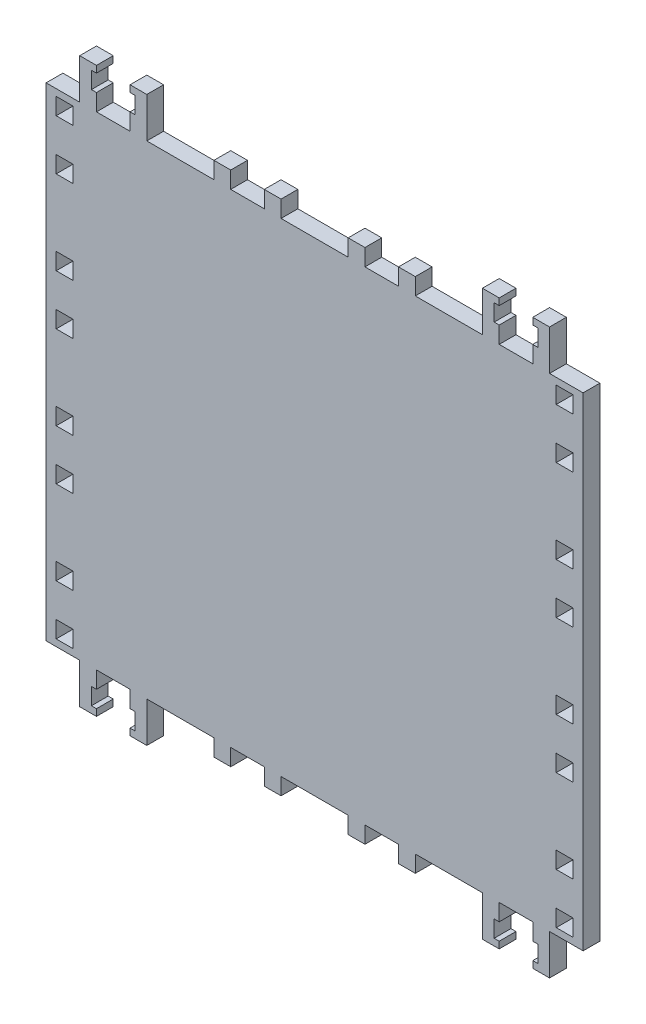
SolidWorks part; units mm, degrees
ref_plane "Plan de face" through (0, 0, 0) normal (0, 0, 1) x (1, 0, 0)
ref_plane "Plan de dessus" through (0, 0, 0) normal (0, 1, 0) x (1, 0, 0)
ref_plane "Plan de droite" through (0, 0, 0) normal (1, 0, 0) x (0, 0, -1)
sketch "Esquisse1" plane through (0, 0, 0) normal (0, 0, 1) x (1, 0, 0)
  line L0 (0, 0) -> (0, 72) construction
  line L1 (-30.7346, 72) -> (18.6998, 72) construction
  line L2 (-80, 144) -> (-70, 144)
  line L3 (-80, 144) -> (-80, 0) construction
  line L4 (-50, 144) -> (-30, 144)
  line L5 (-80, 0) -> (-70, 0)
  line L6 (50, 144) -> (30, 144)
  line L8 (80, 144) -> (70, 144)
  line L9 (10, 144) -> (-10, 144)
  line L10 (80, 0) -> (70, 0)
  line L11 (10, 0) -> (-10, 0)
  line L12 (50, 0) -> (30, 0)
  line L13 (-50, 0) -> (-30, 0)
  line L19 (-80, 0) -> (-80, 144)
  line L26 (80, 144) -> (80, 0)
  point P30 (72, 139.5)
  line B0 (20, 144) -> (20, 132.8925) construction
  line B1 (20, 144) -> (25, 144)
  line B2 (25, 149) -> (30, 149)
  line B3 (30, 149) -> (30, 144)
  line B4 (25, 149) -> (25, 144)
  line B5 (20, 144) -> (15, 144)
  line B6 (15, 144) -> (15, 149)
  line B7 (15, 149) -> (10, 149)
  line B8 (10, 149) -> (10, 144)
  line B9 (-20, 144) -> (-20, 132.8925) construction
  line B10 (-20, 144) -> (-25, 144)
  line B11 (-25, 149) -> (-30, 149)
  line B12 (-30, 149) -> (-30, 144)
  line B13 (-25, 149) -> (-25, 144)
  line B14 (-20, 144) -> (-15, 144)
  line B15 (-15, 144) -> (-15, 149)
  line B16 (-15, 149) -> (-10, 149)
  line B17 (-10, 149) -> (-10, 144)
  line B18 (20, 0) -> (20, 11.1075) construction
  line B19 (20, 0) -> (25, 0)
  line B20 (25, -5) -> (30, -5)
  line B21 (30, -5) -> (30, 0)
  line B22 (25, -5) -> (25, 0)
  line B23 (20, 0) -> (15, 0)
  line B24 (15, 0) -> (15, -5)
  line B25 (15, -5) -> (10, -5)
  line B26 (10, -5) -> (10, 0)
  line B27 (-20, 0) -> (-20, 11.1075) construction
  line B28 (-20, 0) -> (-25, 0)
  line B29 (-25, -5) -> (-30, -5)
  line B30 (-30, -5) -> (-30, 0)
  line B31 (-25, -5) -> (-25, 0)
  line B32 (-20, 0) -> (-15, 0)
  line B33 (-15, 0) -> (-15, -5)
  line B34 (-15, -5) -> (-10, -5)
  line B35 (-10, -5) -> (-10, 0)
  line B36 (74.5, 127) -> (74.5, 137) construction
  line B37 (77, 127) -> (77, 122)
  line B38 (77, 127) -> (72, 127)
  line B39 (72, 127) -> (72, 122)
  line B40 (77, 122) -> (72, 122)
  line B41 (77, 137) -> (77, 142)
  line B42 (77, 137) -> (72, 137)
  line B43 (72, 137) -> (72, 142)
  line B44 (77, 142) -> (72, 142)
  line B45 (74.5, 132) -> (80.7802, 132) construction
  circle B46 centre (74.5, 132) radius 1.5 construction
  line B47 (77, 142) -> (72, 137) construction
  line B48 (77, 127) -> (72, 122) construction
  line B49 (74.5, 87) -> (74.5, 97) construction
  line B50 (77, 87) -> (77, 82)
  line B51 (77, 87) -> (72, 87)
  line B52 (72, 87) -> (72, 82)
  line B53 (77, 82) -> (72, 82)
  line B54 (77, 97) -> (77, 102)
  line B55 (77, 97) -> (72, 97)
  line B56 (72, 97) -> (72, 102)
  line B57 (77, 102) -> (72, 102)
  line B58 (74.5, 92) -> (80.7802, 92) construction
  circle B59 centre (74.5, 92) radius 1.5 construction
  line B60 (77, 102) -> (72, 97) construction
  line B61 (77, 87) -> (72, 82) construction
  line B62 (74.5, 17) -> (74.5, 7) construction
  line B63 (77, 17) -> (77, 22)
  line B64 (77, 17) -> (72, 17)
  line B65 (72, 17) -> (72, 22)
  line B66 (77, 22) -> (72, 22)
  line B67 (77, 7) -> (77, 2)
  line B68 (77, 7) -> (72, 7)
  line B69 (72, 7) -> (72, 2)
  line B70 (77, 2) -> (72, 2)
  line B71 (74.5, 12) -> (80.7802, 12) construction
  circle B72 centre (74.5, 12) radius 1.5 construction
  line B73 (77, 2) -> (72, 7) construction
  line B74 (77, 17) -> (72, 22) construction
  line B75 (74.5, 57) -> (74.5, 47) construction
  line B76 (77, 57) -> (77, 62)
  line B77 (77, 57) -> (72, 57)
  line B78 (72, 57) -> (72, 62)
  line B79 (77, 62) -> (72, 62)
  line B80 (77, 47) -> (77, 42)
  line B81 (77, 47) -> (72, 47)
  line B82 (72, 47) -> (72, 42)
  line B83 (77, 42) -> (72, 42)
  line B84 (74.5, 52) -> (80.7802, 52) construction
  circle B85 centre (74.5, 52) radius 1.5 construction
  line B86 (77, 42) -> (72, 47) construction
  line B87 (77, 57) -> (72, 62) construction
  line B88 (-74.5, 57) -> (-74.5, 47) construction
  line B89 (-77, 57) -> (-77, 62)
  line B90 (-77, 57) -> (-72, 57)
  line B91 (-72, 57) -> (-72, 62)
  line B92 (-77, 62) -> (-72, 62)
  line B93 (-77, 47) -> (-77, 42)
  line B94 (-77, 47) -> (-72, 47)
  line B95 (-72, 47) -> (-72, 42)
  line B96 (-77, 42) -> (-72, 42)
  line B97 (-74.5, 52) -> (-80.7802, 52) construction
  circle B98 centre (-74.5, 52) radius 1.5 construction
  line B99 (-77, 42) -> (-72, 47) construction
  line B100 (-77, 57) -> (-72, 62) construction
  line B101 (-74.5, 127) -> (-74.5, 137) construction
  line B102 (-77, 127) -> (-77, 122)
  line B103 (-77, 127) -> (-72, 127)
  line B104 (-72, 127) -> (-72, 122)
  line B105 (-77, 122) -> (-72, 122)
  line B106 (-77, 137) -> (-77, 142)
  line B107 (-77, 137) -> (-72, 137)
  line B108 (-72, 137) -> (-72, 142)
  line B109 (-77, 142) -> (-72, 142)
  line B110 (-74.5, 132) -> (-80.7802, 132) construction
  circle B111 centre (-74.5, 132) radius 1.5 construction
  line B112 (-77, 142) -> (-72, 137) construction
  line B113 (-77, 127) -> (-72, 122) construction
  line B114 (-74.5, 17) -> (-74.5, 7) construction
  line B115 (-77, 17) -> (-77, 22)
  line B116 (-77, 17) -> (-72, 17)
  line B117 (-72, 17) -> (-72, 22)
  line B118 (-77, 22) -> (-72, 22)
  line B119 (-77, 7) -> (-77, 2)
  line B120 (-77, 7) -> (-72, 7)
  line B121 (-72, 7) -> (-72, 2)
  line B122 (-77, 2) -> (-72, 2)
  line B123 (-74.5, 12) -> (-80.7802, 12) construction
  circle B124 centre (-74.5, 12) radius 1.5 construction
  line B125 (-77, 2) -> (-72, 7) construction
  line B126 (-77, 17) -> (-72, 22) construction
  line B127 (-74.5, 87) -> (-74.5, 97) construction
  line B128 (-77, 87) -> (-77, 82)
  line B129 (-77, 87) -> (-72, 87)
  line B130 (-72, 87) -> (-72, 82)
  line B131 (-77, 82) -> (-72, 82)
  line B132 (-77, 97) -> (-77, 102)
  line B133 (-77, 97) -> (-72, 97)
  line B134 (-72, 97) -> (-72, 102)
  line B135 (-77, 102) -> (-72, 102)
  line B136 (-74.5, 92) -> (-80.7802, 92) construction
  circle B137 centre (-74.5, 92) radius 1.5 construction
  line B138 (-77, 102) -> (-72, 97) construction
  line B139 (-77, 87) -> (-72, 82) construction
  line B140 (-60, 0) -> (-60, 11.865) construction
  line B141 (-60, 0) -> (-65, 0)
  line B142 (-65, -5) -> (-70, -5) construction
  line B143 (-70, -5) -> (-70, 0)
  line B144 (-65, -5) -> (-65, 0)
  line B145 (-60, 0) -> (-55, 0)
  line B146 (-55, 0) -> (-55, -5)
  line B147 (-55, -5) -> (-50, -5) construction
  line B148 (-50, -5) -> (-50, 0)
  line B149 (-70, -5) -> (-70, -12)
  line B150 (-70, -12) -> (-65, -12)
  line B151 (-65, -12) -> (-65, -10)
  line B152 (-65, -10) -> (-66.5, -10)
  line B153 (-66.5, -10) -> (-66.5, -5)
  line B154 (-66.5, -5) -> (-65, -5)
  line B155 (-55, -10) -> (-53.5, -10)
  line B156 (-50, -12) -> (-55, -12)
  line B157 (-55, -12) -> (-55, -10)
  line B158 (-53.5, -10) -> (-53.5, -5)
  line B159 (-50, -5) -> (-50, -12)
  line B160 (-50, -5) -> (-50, 0)
  line B161 (-55, -5) -> (-53.5, -5)
  line B162 (60, 0) -> (60, 11.865) construction
  line B163 (60, 0) -> (65, 0)
  line B164 (65, -5) -> (70, -5) construction
  line B165 (70, -5) -> (70, 0)
  line B166 (65, -5) -> (65, 0)
  line B167 (60, 0) -> (55, 0)
  line B168 (55, 0) -> (55, -5)
  line B169 (55, -5) -> (50, -5) construction
  line B170 (50, -5) -> (50, 0)
  line B171 (70, -5) -> (70, -12)
  line B172 (70, -12) -> (65, -12)
  line B173 (65, -12) -> (65, -10)
  line B174 (65, -10) -> (66.5, -10)
  line B175 (66.5, -10) -> (66.5, -5)
  line B176 (66.5, -5) -> (65, -5)
  line B177 (55, -10) -> (53.5, -10)
  line B178 (50, -12) -> (55, -12)
  line B179 (55, -12) -> (55, -10)
  line B180 (53.5, -10) -> (53.5, -5)
  line B181 (50, -5) -> (50, -12)
  line B182 (50, -5) -> (50, 0)
  line B183 (55, -5) -> (53.5, -5)
  line B184 (-60, 144) -> (-60, 132.135) construction
  line B185 (-60, 144) -> (-65, 144)
  line B186 (-65, 149) -> (-70, 149) construction
  line B187 (-70, 149) -> (-70, 144)
  line B188 (-65, 149) -> (-65, 144)
  line B189 (-60, 144) -> (-55, 144)
  line B190 (-55, 144) -> (-55, 149)
  line B191 (-55, 149) -> (-50, 149) construction
  line B192 (-50, 149) -> (-50, 144)
  line B193 (-70, 149) -> (-70, 156)
  line B194 (-70, 156) -> (-65, 156)
  line B195 (-65, 156) -> (-65, 154)
  line B196 (-65, 154) -> (-66.5, 154)
  line B197 (-66.5, 154) -> (-66.5, 149)
  line B198 (-66.5, 149) -> (-65, 149)
  line B199 (-55, 154) -> (-53.5, 154)
  line B200 (-50, 156) -> (-55, 156)
  line B201 (-55, 156) -> (-55, 154)
  line B202 (-53.5, 154) -> (-53.5, 149)
  line B203 (-50, 149) -> (-50, 156)
  line B204 (-50, 149) -> (-50, 144)
  line B205 (-55, 149) -> (-53.5, 149)
  line B206 (60, 144) -> (60, 132.135) construction
  line B207 (60, 144) -> (65, 144)
  line B208 (65, 149) -> (70, 149) construction
  line B209 (70, 149) -> (70, 144)
  line B210 (65, 149) -> (65, 144)
  line B211 (60, 144) -> (55, 144)
  line B212 (55, 144) -> (55, 149)
  line B213 (55, 149) -> (50, 149) construction
  line B214 (50, 149) -> (50, 144)
  line B215 (70, 149) -> (70, 156)
  line B216 (70, 156) -> (65, 156)
  line B217 (65, 156) -> (65, 154)
  line B218 (65, 154) -> (66.5, 154)
  line B219 (66.5, 154) -> (66.5, 149)
  line B220 (66.5, 149) -> (65, 149)
  line B221 (55, 154) -> (53.5, 154)
  line B222 (50, 156) -> (55, 156)
  line B223 (55, 156) -> (55, 154)
  line B224 (53.5, 154) -> (53.5, 149)
  line B225 (50, 149) -> (50, 156)
  line B226 (50, 149) -> (50, 144)
  line B227 (55, 149) -> (53.5, 149)
  dimension "D1" = 40
  dimension "D2" = 160
  dimension "D3" = 160
  dimension "D4" = 144
  dimension "D5" = 72
  dimension "D6" = 60
  dimension "D7" = 40
  dimension "D8" = 25.4951
  dimension "D9" = 40
  dimension "D10" = 40
  dimension "D12" = 40
  dimension "D13" = 144
sketch_block_instance "Insert M3 plots ep 5mm-4"
sketch_block "Insert M3 plots ep 5mm" parameters "D1"=10, "D2"=5, "D3"=5
sketch_block_instance "Insert M3 plots ep 5mm-5"
sketch_block_instance "Insert M3 plots ep 5mm-10"
sketch_block_instance "Insert M3 plots ep 5mm-11"
sketch_block_instance "Trou M3 plots 5mm-59"
sketch_block "Trou M3 plots 5mm" parameters "D2"=3, "D5"=3, "D1"=5, "D3"=5, "D4"=8
sketch_block_instance "Trou M3 plots 5mm-60"
sketch_block_instance "Trou M3 plots 5mm-61"
sketch_block_instance "Trou M3 plots 5mm-62"
sketch_block_instance "Trou M3 plots 5mm-63"
sketch_block_instance "Trou M3 plots 5mm-64"
sketch_block_instance "Trou M3 plots 5mm-65"
sketch_block_instance "Trou M3 plots 5mm-66"
sketch_block_instance "Insert plots ep 5mm avec ergots-1"
sketch_block "Insert plots ep 5mm avec ergots" parameters "D1"=10, "D2"=5, "D3"=5, "D4"=5, "D5"=2, "D6"=1.5, "D7"=2, "D8"=2, "D9"=2.0716, "D10"=2
sketch_block_instance "Insert plots ep 5mm avec ergots-3"
sketch_block_instance "Insert plots ep 5mm avec ergots-4"
sketch_block_instance "Insert plots ep 5mm avec ergots-5"
extrude "Boss.-Extru.1" add sketch "Esquisse1" along normal blind 5
